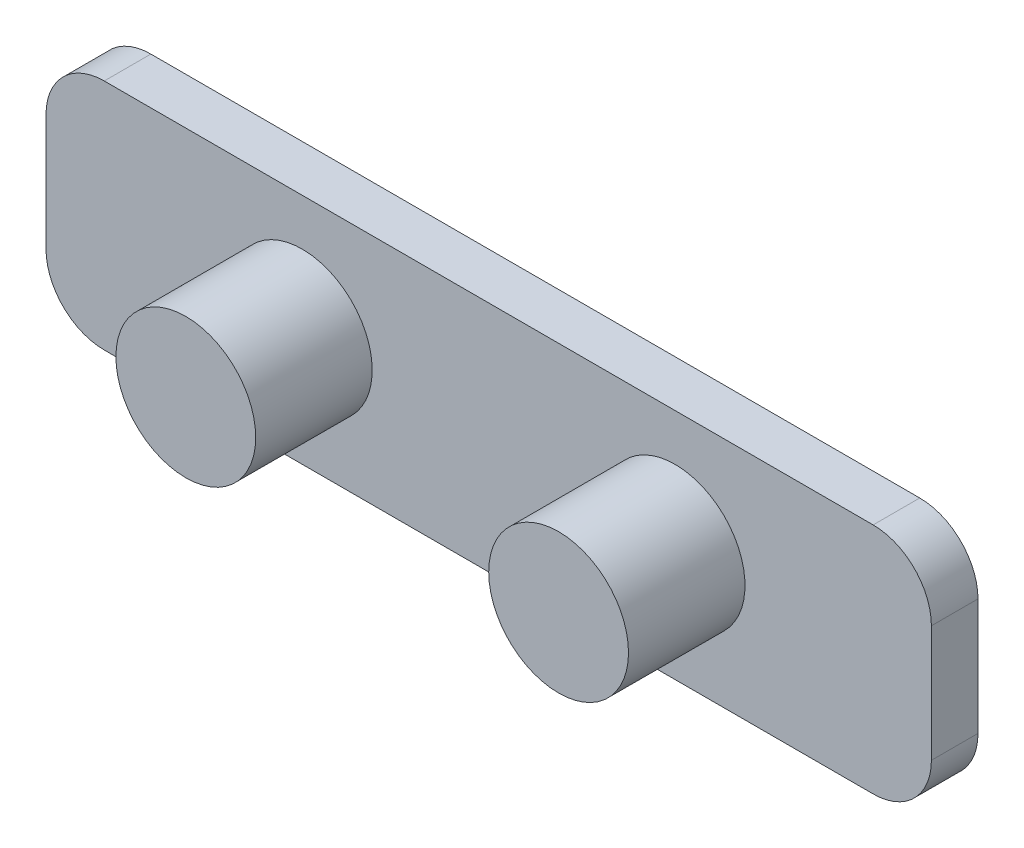
SolidWorks part; units mm, degrees
ref_plane "Front Plane" through (0, 0, 0) normal (0, 0, 1) x (1, 0, 0)
ref_plane "Top Plane" through (0, 0, 0) normal (0, 1, 0) x (1, 0, 0)
ref_plane "Right Plane" through (0, 0, 0) normal (1, 0, 0) x (0, 0, -1)
sketch "Sketch1" plane through (0, 0, 0) normal (0, 0, 1) x (1, 0, 0)
  line L1 (-5.3133, 3.8394) -> (27.6867, 3.8394)
  line L2 (-7.8133, 1.3394) -> (-7.8133, -3.6606)
  line L3 (-5.3133, -6.1606) -> (27.6867, -6.1606)
  line L4 (30.1867, 1.3394) -> (30.1867, -3.6606)
  arc A0 (-7.8133, 1.3394) -> (-5.3133, 3.8394) centre (-5.3133, 1.3394) cw
  arc A1 (-7.8133, -3.6606) -> (-5.3133, -6.1606) centre (-5.3133, -3.6606) ccw
  arc A2 (30.1867, -3.6606) -> (27.6867, -6.1606) centre (27.6867, -3.6606) cw
  arc A3 (30.1867, 1.3394) -> (27.6867, 3.8394) centre (27.6867, 1.3394) ccw
  point P6 (-7.8133, 3.8394)
  point P9 (-7.8133, -6.1606)
  point P14 (30.1867, 3.8394)
  dimension "D3" = 2.5
  dimension "D4" = 2.5
  dimension "D5" = 2.5
  dimension "D6" = 2.5
  dimension "D1" = 38
  dimension "D2" = 10
extrude "Boss-Extrude1" add sketch "Sketch1" along normal blind 2
sketch "Sketch2" plane through (0, 0, 2) normal (0, 0, 1) x (1, 0, 0)
  line L0 (-5.3133, -6.1606) -> (27.6867, -6.1606) construction
  line L1 (-7.8133, 1.3394) -> (-7.8133, -3.6606) construction
  circle A0 centre (3.1867, -1.1606) radius 3
  circle A1 centre (19.1867, -1.1606) radius 3
  dimension "D2" = 6
  dimension "D1" = 16
  dimension "D3" = 5
  dimension "D4" = 11
extrude "Boss-Extrude2" add sketch "Sketch2" along normal blind 5
